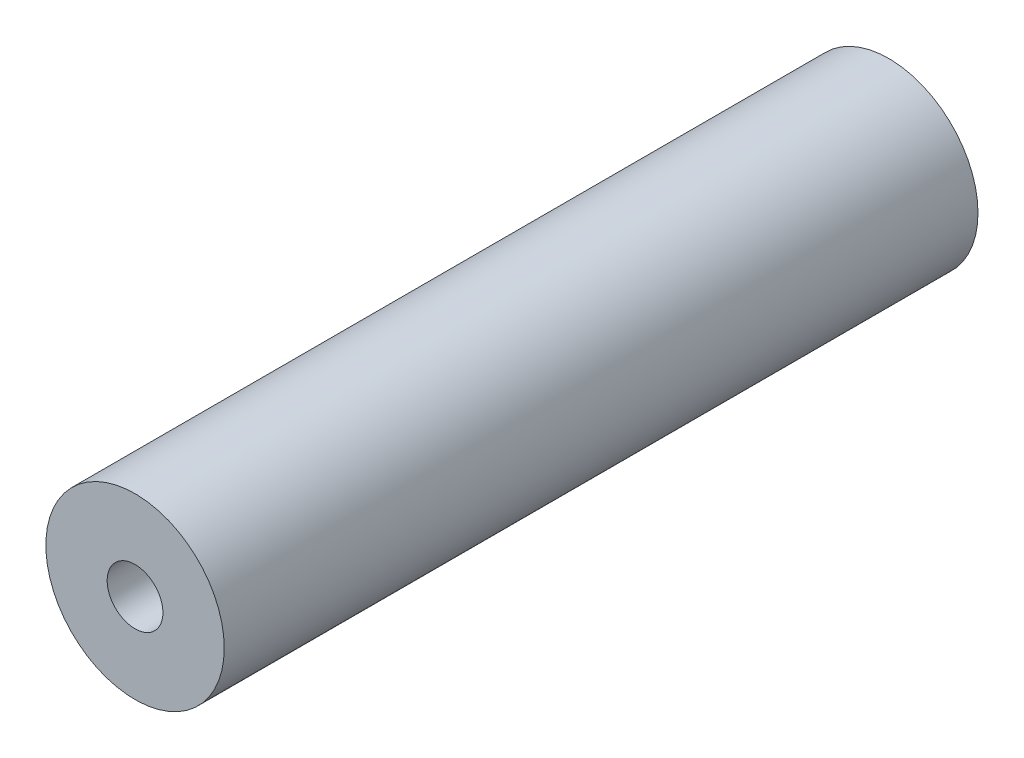
SolidWorks part; units mm, degrees
ref_plane "Front Plane" through (0, 0, 0) normal (0, 0, 1) x (1, 0, 0)
ref_plane "Top Plane" through (0, 0, 0) normal (0, 1, 0) x (1, 0, 0)
ref_plane "Right Plane" through (0, 0, 0) normal (1, 0, 0) x (0, 0, -1)
sketch "Sketch1" plane through (0, 0, 0) normal (0, 0, 1) x (1, 0, 0)
  circle A0 centre (0, 0) radius 4
  dimension "D1" = 8
extrude "Boss-Extrude1" add sketch "Sketch1" along normal blind 33.8
sketch "Sketch2" plane through (0, 0, 33.8) normal (0, 0, 1) x (1, 0, 0)
  point P0 (0, 0)
hole_wizard "Tap Drill for M3 Tap1" positions "Sketch2" profile "Sketch3" hole size "M3" standard "ISO" end condition through all
sketch "Sketch3" plane through (0, 0, 33.8) normal (1, 0, 0) x (0, -1, 0)
  line L0 (0, 0) -> (0, 33.8)
  line L1 (0, 33.8) -> (1.25, 33.8)
  line L2 (1.25, 33.8) -> (1.25, 0)
  line L5 (1.25, 0) -> (0, 0)
  line L11 (0, -6.35) -> (0, 107.95) construction
  dimension "Thru Hole Dia." = 2.5
  dimension "Thru Hole Depth" = 33.8
